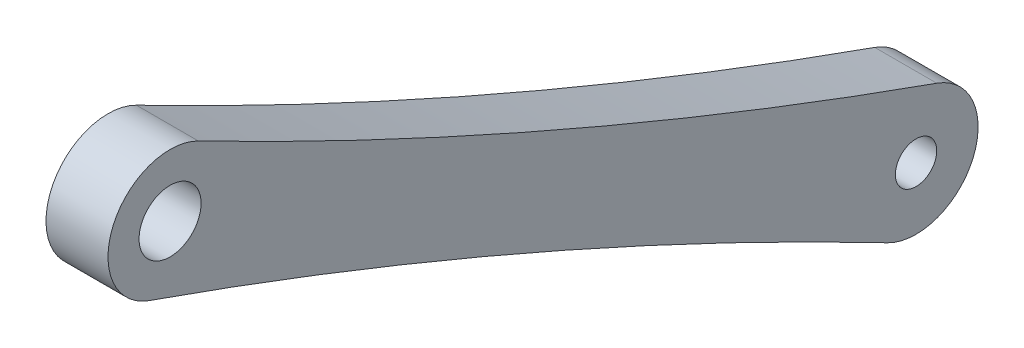
SolidWorks part; units mm, degrees
ref_plane "Front Plane" through (0, 0, 0) normal (1, 0, 0) x (0, 1, 0)
ref_plane "Top Plane" through (0, 0, 0) normal (0, 0, 1) x (0, 1, 0)
ref_plane "Right Plane" through (0, 0, 0) normal (0, 1, 0) x (-1, 0, 0)
sketch "Sketch1" plane through (0, 0, 0) normal (1, 0, 0) x (0, 1, 0)
  line L0 (34.9544, 81.6423) -> (174.7722, 81.6423) construction
  line L1 (43.2231, 11.8043) -> (59.6898, 57.9545)
  line L2 (59.6898, 57.9545) -> (27.5087, 75.5973)
  line L3 (27.5087, 75.5973) -> (43.2231, 11.8043)
  line L4 (59.6898, 57.9545) -> (114.4197, 86.8725)
  line L5 (114.4197, 86.8725) -> (92.4757, 131.7998)
  line L6 (92.4757, 131.7998) -> (75.2816, 94.0293)
  line L7 (75.2816, 94.0293) -> (59.6898, 57.9545)
  line L8 (27.5087, 75.5973) -> (39.9439, 112.9835)
  line L9 (39.9439, 112.9835) -> (92.4757, 131.7998)
  line L10 (39.9439, 112.9835) -> (75.2816, 94.0293)
  line L11 (114.4197, 86.8725) -> (113.2816, 101.8293)
  dimension "D1" = 49
  dimension "D2" = 65.7
  dimension "D3" = 36.7
  dimension "D4" = 61.9
  dimension "D5" = 50
  dimension "D6" = 41.5
  dimension "D7" = 39.3
  dimension "D8" = 55.8
  dimension "D9" = 39.4
  dimension "D10" = 40.1
  dimension "D11" = 15
  dimension "D12" = 7.8
  dimension "D13" = 38
sketch "Sketch2" plane through (0, 0, 0) normal (1, 0, 0) x (0, 1, 0)
  arc A0 (52.2618, 64.6497) -> (69.6559, 57.1318) centre (59.6898, 57.9545) ccw
  arc A1 (82.7096, 87.3342) -> (65.3155, 94.852) centre (75.2816, 94.0293) ccw
  arc A2 (82.7096, 87.3342) -> (69.6559, 57.1318) centre (120.9123, 52.9006) ccw
  arc A3 (52.2618, 64.6497) -> (65.3155, 94.852) centre (14.0591, 99.0833) ccw
  circle A4 centre (75.2816, 94.0293) radius 1.375
  circle A5 centre (59.6898, 57.9545) radius 1
  dimension "D1" = 20
  dimension "D2" = 2.75
  dimension "D3" = 2
extrude "Boss-Extrude1" add sketch "Sketch2" along normal blind 3
scale "Scale1" scale about centroid uniform scaling yes scale factor 2
sketch "Sketch3" plane through (4.5, 0, 0) normal (1, 0, 0) x (0, 1, 0)
  circle A0 centre (83.1008, 112.1206) radius 3
  dimension "D1" = 6
extrude "Cut-Extrude1" cut sketch "Sketch3" against normal through all
sketch "Sketch4" plane through (4.5, 0, 0) normal (1, 0, 0) x (0, 1, 0)
  arc A0 (88.4362, 109.376) -> (77.4377, 114.1031) centre (83.1008, 112.1206) ccw
  arc A1 (46.5931, 42.7375) -> (57.5722, 37.9657) centre (51.9173, 39.9711) ccw
  arc A2 (46.5771, 42.7068) -> (77.4377, 114.1031) centre (-438.0966, 294.5719) ccw
  arc A3 (88.6398, 109.7713) -> (57.4712, 37.6808) centre (603.8705, -155.773) ccw
  arc A12 (29.6333, 60.0565) -> (53.2025, 114.5888) centre (-39.3442, 122.2286) ccw
  arc A13 (29.6333, 60.0565) -> (81.8156, 37.503) centre (51.9173, 39.9711) ccw
  arc A14 (105.3848, 92.0352) -> (81.8156, 37.503) centre (174.3623, 29.8632) ccw
  arc A15 (105.3848, 92.0352) -> (53.2025, 114.5888) centre (83.1008, 112.1206) ccw
  arc A16 (29.6333, 60.0565) -> (53.2025, 114.5888) centre (-39.3442, 122.2286) ccw
  arc A17 (29.6333, 60.0565) -> (81.8156, 37.503) centre (51.9173, 39.9711) ccw
  arc A18 (105.3848, 92.0352) -> (81.8156, 37.503) centre (174.3623, 29.8632) ccw
  arc A19 (105.3848, 92.0352) -> (53.2025, 114.5888) centre (83.1008, 112.1206) ccw
  spline S0 degree 3 poles (46.5771, 42.7068) (46.5718, 42.6963) (46.5666, 42.6859) (46.5613, 42.6755) knots 0.950045 0.950045 0.950045 0.950045 0.950285 0.950285 0.950285 0.950285
  point P17 (160.1316, 36.0138)
  point P19 (287.0128, -18.8251)
  point P21 (419.6563, -76.1544)
  point P23 (-140.4433, 165.9242)
  point P24 (-438.0966, 294.5719)
  point P25 (603.8705, -155.773)
  dimension "D1" = 12
  dimension "D2" = 12
  dimension "D3" = 579.6348
  dimension "D4" = 546.2093
  dimension "D5" = 10
extrude "Cut-Extrude2" cut sketch "Sketch4" against normal through all both and the other way through all
